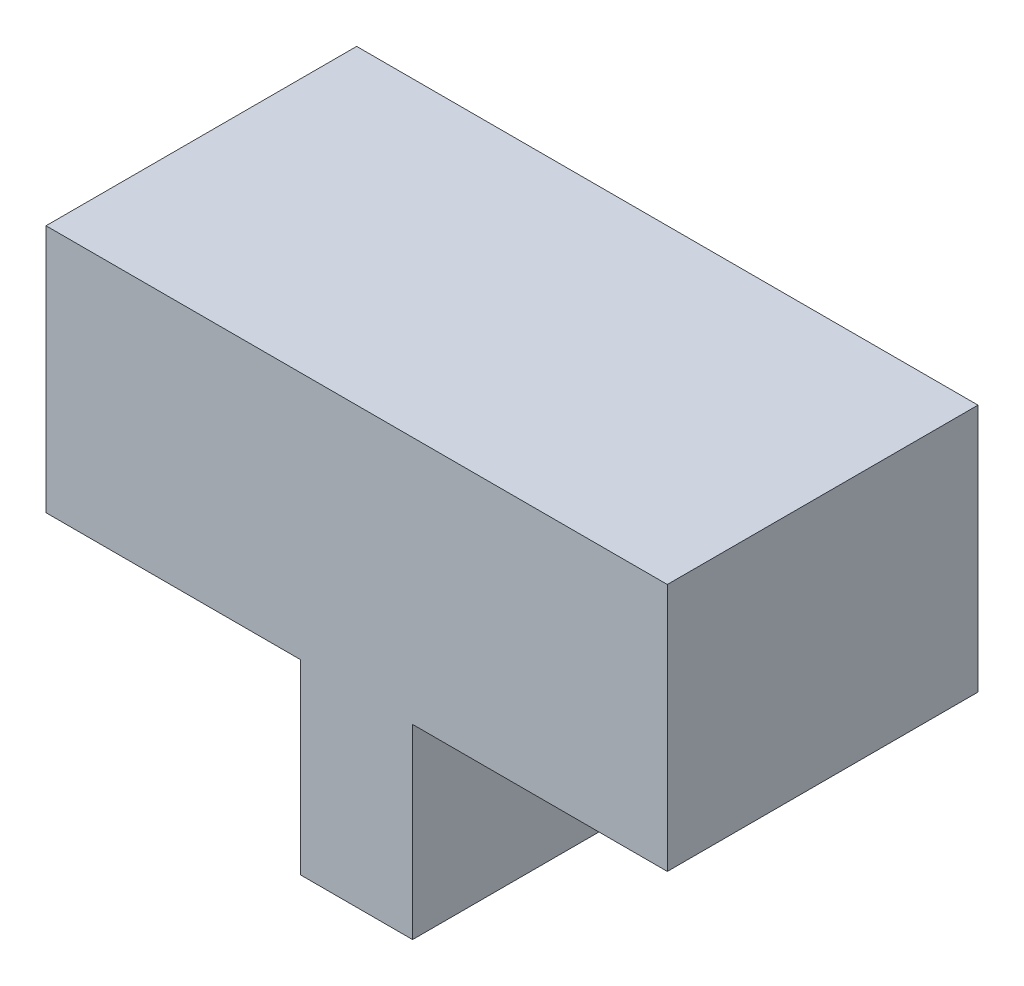
SolidWorks part; units mm, degrees
ref_plane "Front Plane" through (0, 0, 0) normal (0, 0, 1) x (1, 0, 0)
ref_plane "Top Plane" through (0, 0, 0) normal (0, 1, 0) x (1, 0, 0)
ref_plane "Right Plane" through (0, 0, 0) normal (1, 0, 0) x (0, 0, -1)
sketch "Sketch1" plane through (0, 0, 0) normal (0, 0, 1) x (1, 0, 0)
  line L0 (-1.8, 9.5) -> (-1.8, 3.5)
  line L5 (0, -2.7351) -> (0, 17.5) construction
  line L6 (10, 17.5) -> (-10, 17.5)
  line L7 (-10, 17.5) -> (-10, 9.5)
  line L8 (-10, 9.5) -> (-1.8, 9.5)
  line L12 (1.8, 9.5) -> (1.8, 3.5)
  line L13 (10, 9.5) -> (1.8, 9.5)
  line L14 (10, 17.5) -> (10, 9.5)
  line L15 (-1.8, 3.5) -> (1.8, 3.5)
  dimension "D1" = 8
  dimension "6" = 6
  dimension "D3" = 10
  dimension "D4" = 1.8
extrude "Boss-Extrude1" add sketch "Sketch1" along normal blind 10
